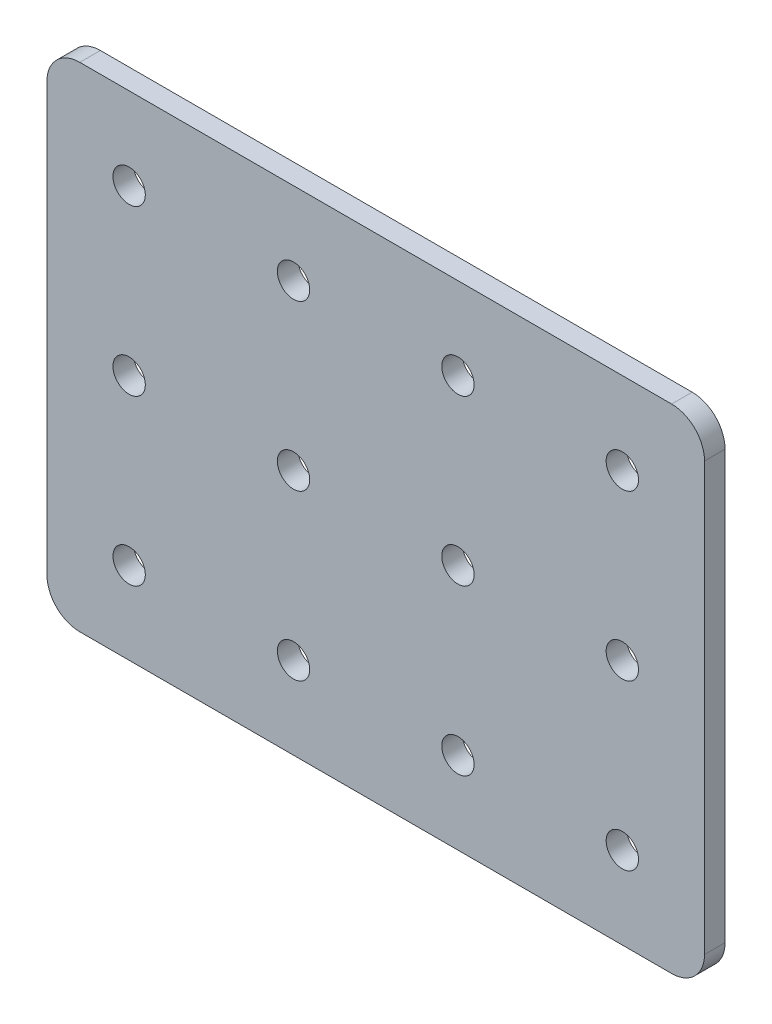
SolidWorks part; units mm, degrees
ref_plane "Front Plane" through (0, 0, 0) normal (0, 0, 1) x (1, 0, 0)
ref_plane "Top Plane" through (0, 0, 0) normal (0, 1, 0) x (1, 0, 0)
ref_plane "Right Plane" through (0, 0, 0) normal (1, 0, 0) x (0, 0, -1)
sketch "Sketch1" plane through (0, 0, 0) normal (0, 0, 1) x (1, 0, 0)
  line L1 (71.12, 76.2) -> (-20.32, 76.2)
  line L2 (76.2, 71.12) -> (76.2, 5.08)
  line L3 (71.12, 0) -> (-20.32, 0)
  line L4 (-25.4, 71.12) -> (-25.4, 5.08)
  line L5 (-25.4, 355.6) -> (-25.4, 0) construction
  line L6 (-736.6, 0) -> (25.4, 0) construction
  circle A7 centre (38.1, 12.7) radius 2.5
  circle A8 centre (12.7, 12.7) radius 2.5
  circle A9 centre (-12.7, 12.7) radius 2.5
  circle A13 centre (63.5, 12.7) radius 2.5
  arc A14 (76.2, 5.08) -> (71.12, 0) centre (71.12, 5.08) cw
  arc A15 (-20.32, 0) -> (-25.4, 5.08) centre (-20.32, 5.08) cw
  arc A16 (71.12, 76.2) -> (76.2, 71.12) centre (71.12, 71.12) cw
  arc A17 (-20.32, 76.2) -> (-25.4, 71.12) centre (-20.32, 71.12) ccw
  circle A18 centre (38.1, 12.7) radius 2.5
  circle A19 centre (12.7, 12.7) radius 2.5
  circle A20 centre (-12.7, 12.7) radius 2.5
  circle A21 centre (38.1, 38.1) radius 2.5
  circle A22 centre (12.7, 38.1) radius 2.5
  circle A23 centre (-12.7, 38.1) radius 2.5
  circle A24 centre (38.1, 63.5) radius 2.5
  circle A25 centre (12.7, 63.5) radius 2.5
  circle A26 centre (-12.7, 63.5) radius 2.5
  circle A27 centre (63.5, 38.1) radius 2.5
  circle A28 centre (63.5, 63.5) radius 2.5
  point P44 (76.2, 76.2)
  dimension "D3" = 5.08
  dimension "D1" = 4
  dimension "D2" = 3
extrude "Boss-Extrude1" add sketch "Sketch1" against normal blind 3.175 from surface at -3248.025 contours L1 A17 L4 A15 L3 A14 L2 A16 A28 A27 A26 A25 A24 A23 A22 A21 A7 A8 A9 A13
